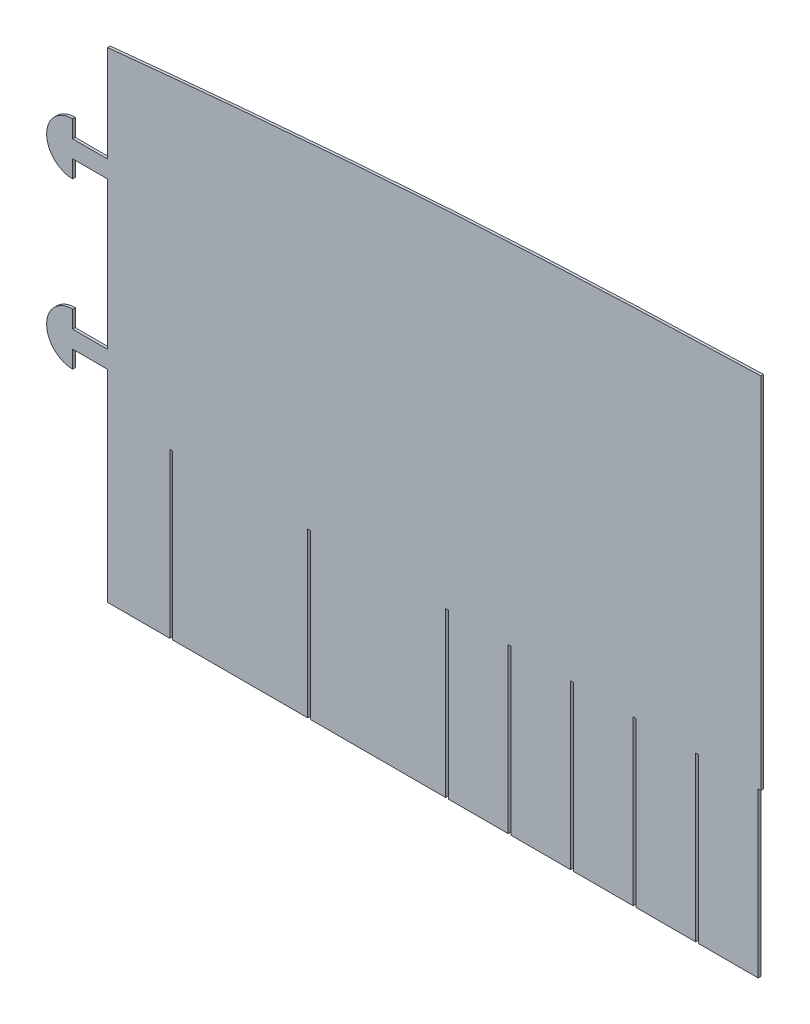
SolidWorks part; units mm, degrees
ref_plane "Front Plane" through (0, 0, 0) normal (0, 0, 1) x (1, 0, 0)
ref_plane "Top Plane" through (0, 0, 0) normal (0, 1, 0) x (1, 0, 0)
ref_plane "Right Plane" through (0, 0, 0) normal (1, 0, 0) x (0, 0, -1)
sketch "Model" plane through (0, 0, 0) normal (0, 0, 1) x (1, 0, 0)
  line L0 (1295.101, 0) -> (1295.101, 232.6278)
  line L1 (1295.101, 0) -> (1366.901, 0)
  line L2 (1366.901, 188.6103) -> (1366.901, 0)
  line L3 (1369.901, 188.6103) -> (1366.901, 188.6103)
  line L4 (1369.901, 0) -> (1369.901, 188.6103)
  line L5 (1369.901, 0) -> (1525.901, 0)
  line L6 (1525.901, 188.6103) -> (1525.901, 0)
  line L7 (1528.901, 188.6103) -> (1525.901, 188.6103)
  line L8 (1528.901, 0) -> (1528.901, 188.6103)
  line L9 (1528.901, 0) -> (1684.901, 0)
  line L10 (1684.901, 188.6103) -> (1684.901, 0)
  line L11 (1687.901, 188.6103) -> (1684.901, 188.6103)
  line L12 (1687.901, 0) -> (1687.901, 188.6103)
  line L13 (1687.901, 0) -> (1756.9435, 0)
  line L14 (1756.9435, 188.6103) -> (1756.9435, 0)
  line L15 (1759.9435, 188.6103) -> (1756.9435, 188.6103)
  line L16 (1759.9435, 0) -> (1759.9435, 188.6103)
  line L17 (1759.9435, 0) -> (1828.986, 0)
  line L18 (1828.986, 188.6103) -> (1828.986, 0)
  line L19 (1831.986, 188.6103) -> (1828.986, 188.6103)
  line L20 (1831.986, 0) -> (1831.986, 188.6103)
  line L21 (1831.986, 0) -> (1901.0286, 0)
  line L22 (1901.0286, 188.6103) -> (1901.0286, 0)
  line L23 (1904.0286, 188.6103) -> (1901.0286, 188.6103)
  line L24 (1904.0286, 0) -> (1904.0286, 188.6103)
  line L25 (1904.0286, 0) -> (1973.0711, 0)
  line L26 (1973.0711, 188.6103) -> (1973.0711, 0)
  line L27 (1976.0711, 188.6103) -> (1973.0711, 188.6103)
  line L28 (1976.0711, 0) -> (1976.0711, 188.6103)
  line L29 (1976.0711, 0) -> (2045.1136, 0)
  line L30 (2045.1136, 188.6103) -> (2045.1136, 0)
  line L31 (2048.1136, 188.6103) -> (2045.1136, 188.6103)
  line L32 (2048.1136, 188.6103) -> (2048.1136, 602.6278)
  line L33 (1295.101, 442.6278) -> (1295.101, 553.8894)
  line L34 (1295.101, 442.6278) -> (1254.901, 442.6278)
  line L35 (1254.901, 462.6278) -> (1254.901, 442.6278)
  line L36 (1254.901, 422.6278) -> (1254.901, 402.6278)
  line L37 (1295.101, 422.6278) -> (1254.901, 422.6278)
  line L38 (1295.101, 252.6278) -> (1295.101, 422.6278)
  line L39 (1254.901, 252.6278) -> (1295.101, 252.6278)
  line L40 (1254.901, 272.6278) -> (1254.901, 252.6278)
  line L41 (1254.901, 232.6278) -> (1254.901, 212.6278)
  line L42 (1295.101, 232.6278) -> (1254.901, 232.6278)
  arc A0 (1254.901, 462.6278) -> (1254.901, 402.6278) centre (1254.901, 432.6278) ccw
  arc A1 (1254.901, 272.6278) -> (1254.901, 212.6278) centre (1254.901, 242.6278) ccw
  spline S0 degree 3 poles (2048.1136, 602.6278) (1934.5964, 599.1114) (1718.6049, 592.1824) (1441.4869, 568.5414) (1295.101, 553.8894) knots 0.033635 0.033635 0.033635 0.033635 0.070138 0.108742 0.108742 0.108742 0.108742
extrude "Boss-Extrude1" add sketch "Model" along normal blind 3
